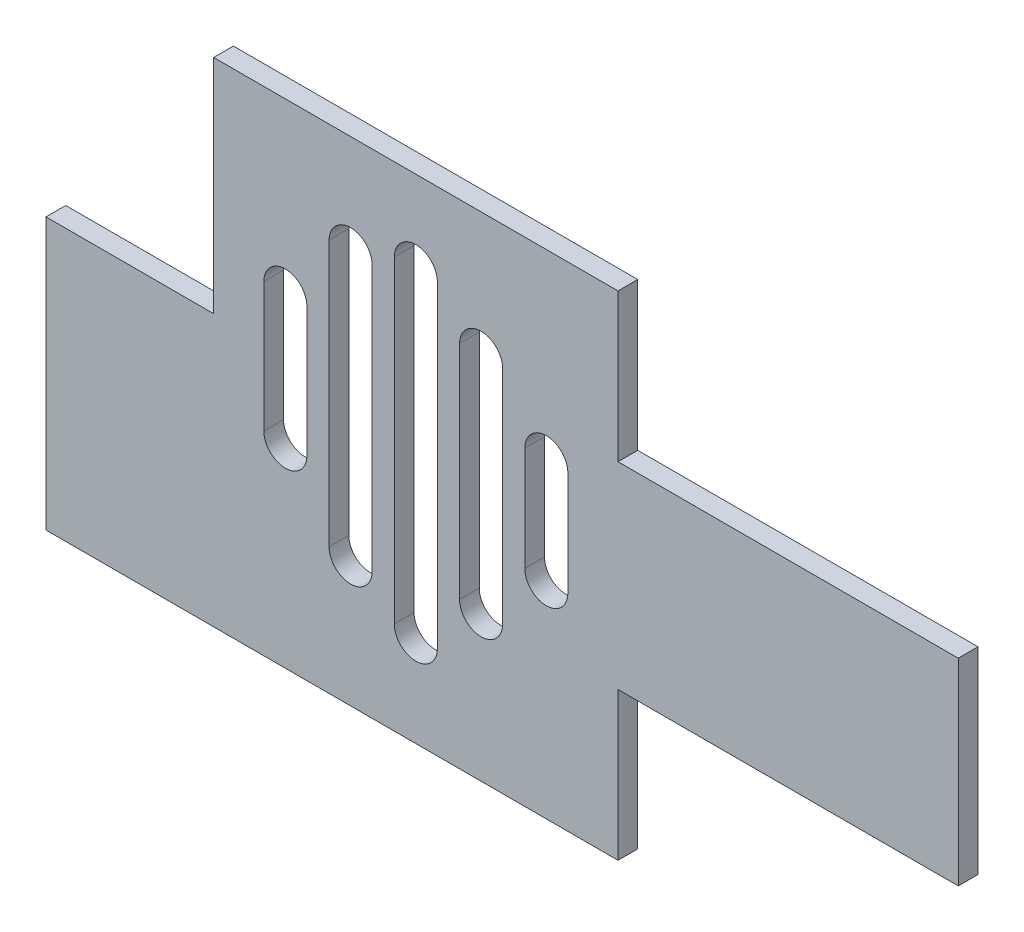
SolidWorks part; units mm, degrees
ref_plane "Front Plane" through (0, 0, 0) normal (0, 0, 1) x (1, 0, 0)
ref_plane "Top Plane" through (0, 0, 0) normal (0, 1, 0) x (1, 0, 0)
ref_plane "Right Plane" through (0, 0, 0) normal (1, 0, 0) x (0, 0, -1)
sketch "Sketch1" plane through (0, 0, 0) normal (0, 0, 1) x (1, 0, 0)
  line L0 (0, 33.2683) -> (0, -31.1612) construction
  line L1 (-75, -50) -> (75, -50) construction
  line L3 (-75, 50) -> (75, 50) construction
  line L5 (-75, -50) -> (75, 50) construction
  line L6 (-75, 50) -> (75, -50) construction
  line L7 (4.3648, 33.2683) -> (4.3648, -31.1612)
  line L8 (-4.3648, 33.2683) -> (-4.3648, -31.1612)
  line L9 (-13.2297, 29.6339) -> (-13.2297, -24.2226) construction
  line L10 (-8.8648, 29.6339) -> (-8.8648, -24.2226)
  line L11 (-17.5945, 29.6339) -> (-17.5945, -24.2226)
  line L12 (13.2297, 24.6777) -> (13.2297, -20.2577) construction
  line L13 (17.5945, 24.6777) -> (17.5945, -20.2577)
  line L14 (8.8648, 24.6777) -> (8.8648, -20.2577)
  line L15 (-26.4594, 15.7567) -> (-26.4594, -10.5107) construction
  line L16 (-22.0945, 15.7567) -> (-22.0945, -10.5107)
  line L17 (-30.8242, 15.7567) -> (-30.8242, -10.5107)
  line L18 (26.4594, 12.9483) -> (26.4594, -8.1978) construction
  line L19 (30.8242, 12.9483) -> (30.8242, -8.1978)
  line L20 (22.0945, 12.9483) -> (22.0945, -8.1978)
  line L21 (0, 80.4433) -> (0, -75.6846) construction
  line L22 (56, 35) -> (60, 35) construction
  line L23 (56, 35) -> (56, 20) construction
  line L24 (56, 20) -> (60, 20) construction
  line L25 (60, 35) -> (60, 20) construction
  line L26 (-110.7456, 0) -> (128.9906, 0) construction
  line L27 (56, -20) -> (60, -20) construction
  line L28 (56, -35) -> (56, -20) construction
  line L29 (60, -35) -> (60, -20) construction
  line L30 (56, -35) -> (60, -35) construction
  line L35 (-56, 20) -> (-60, 20) construction
  line L36 (-56, 35) -> (-56, 20) construction
  line L37 (-60, 35) -> (-60, 20) construction
  line L38 (-56, 35) -> (-60, 35) construction
  line L42 (75, 50) -> (110, 50) construction
  line L51 (110, 50) -> (110, -50) construction
  line L52 (110, -50) -> (75, -50) construction
  line L53 (-75, 50) -> (-75, -50) construction
  line L54 (105, 35) -> (101, 35) construction
  line L55 (105, 35) -> (105, 20) construction
  line L56 (105, 20) -> (101, 20) construction
  line L57 (101, 35) -> (101, 20) construction
  line L59 (105, -20) -> (105, -35) construction
  line L60 (105, -35) -> (101, -35) construction
  line L61 (101, -20) -> (101, -35) construction
  line L62 (-41, 50) -> (-41, 5)
  line L63 (-41, 5) -> (-75, 5)
  line L64 (-41, 50) -> (75, 50) construction
  line L65 (-75, 5) -> (-75, -50)
  line L66 (41, 50) -> (41, 20)
  line L67 (41, 20) -> (110, 20)
  line L68 (110, 20) -> (110, -20)
  line L69 (110, -20) -> (41, -20)
  line L70 (41, -20) -> (41, -50)
  line L71 (41, 50) -> (-41, 50)
  line L72 (41, -50) -> (-75, -50)
  line L73 (101, -20) -> (105, -20) construction
  arc A1 (4.3648, 33.2683) -> (-4.3648, 33.2683) centre (0, 33.2683) ccw
  arc A2 (-4.3648, -31.1612) -> (4.3648, -31.1612) centre (0, -31.1612) ccw
  arc A3 (-8.8648, 29.6339) -> (-17.5945, 29.6339) centre (-13.2297, 29.6339) ccw
  arc A4 (-17.5945, -24.2226) -> (-8.8648, -24.2226) centre (-13.2297, -24.2226) ccw
  arc A5 (17.5945, 24.6777) -> (8.8648, 24.6777) centre (13.2297, 24.6777) ccw
  arc A6 (8.8648, -20.2577) -> (17.5945, -20.2577) centre (13.2297, -20.2577) ccw
  arc A7 (-22.0945, 15.7567) -> (-30.8242, 15.7567) centre (-26.4594, 15.7567) ccw
  arc A8 (-30.8242, -10.5107) -> (-22.0945, -10.5107) centre (-26.4594, -10.5107) ccw
  arc A9 (30.8242, 12.9483) -> (22.0945, 12.9483) centre (26.4594, 12.9483) ccw
  arc A10 (22.0945, -8.1978) -> (30.8242, -8.1978) centre (26.4594, -8.1978) ccw
  point P0 (0, 0)
  point P8 (0, 1.0536)
  point P13 (-13.2297, 2.7056)
  point P20 (13.2297, 2.21)
  point P27 (-26.4594, 2.623)
  point P34 (26.4594, 2.3752)
  dimension "D3" = 4.3648
  dimension "D4" = 4.3648
  dimension "D5" = 4.3648
  dimension "D6" = 4.3648
  dimension "D7" = 4.3648
  dimension "D1" = 100
  dimension "D2" = 150
  dimension "D8" = 4.5
  dimension "D9" = 4.5
  dimension "D10" = 4.5
  dimension "D11" = 4.5
  dimension "D12" = 4
  dimension "D13" = 15
  dimension "D14" = 35
  dimension "D15" = 15
  dimension "D16" = 15
  dimension "D17" = 5
  dimension "D18" = 5
  dimension "D19" = 15
  dimension "D20" = 0
  dimension "D21" = 15
  dimension "D22" = 0
extrude "Boss-Extrude1" add sketch "Sketch1" along normal blind 4
